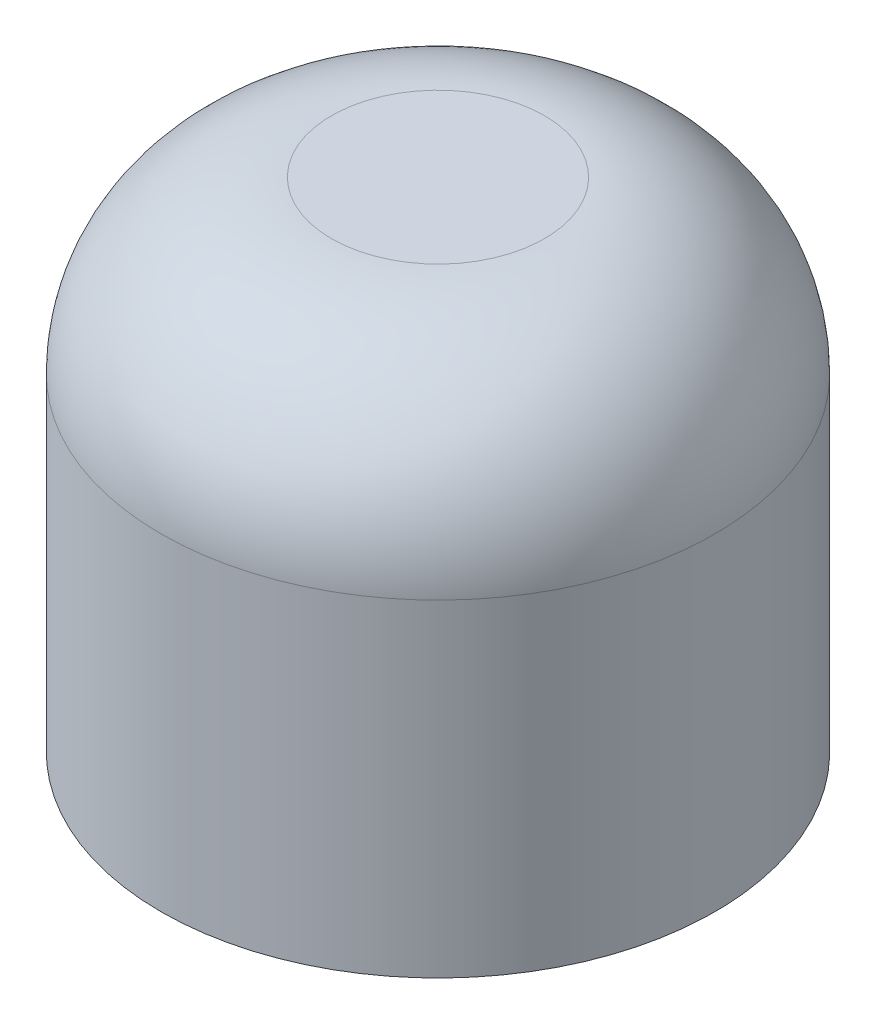
SolidWorks part; units mm, degrees
ref_plane "Front Plane" through (0, 0, 0) normal (0, 0, 1) x (1, 0, 0)
ref_plane "Top Plane" through (0, 0, 0) normal (0, 1, 0) x (1, 0, 0)
ref_plane "Right Plane" through (0, 0, 0) normal (1, 0, 0) x (0, 0, -1)
sketch "Sketch1" plane through (0, 0, 0) normal (0, 1, 0) x (1, 0, 0)
  circle A0 centre (0, 0) radius 13.65
  circle A1 centre (0, 0) radius 16.25
  dimension "D1" = 27.3
  dimension "D2" = 32.5
extrude "Boss-Extrude1" add sketch "Sketch1" along normal blind 24
sketch "Sketch2" plane through (0, 24, 0) normal (0, 1, 0) x (1, 0, 0)
  circle A0 centre (0, 0) radius 14.95
  dimension "D1" = 29.9
chamfer "Chamfer1" distance 1 angle 45 1 edges at (0, 0, 13.65)
sketch "Sketch3" plane through (0, 24, 0) normal (0, 1, 0) x (1, 0, 0)
  circle A0 centre (0, 0) radius 16.25
extrude "Boss-Extrude3" add sketch "Sketch3" along normal blind 5.2
fillet "Fillet3" radius 10 1 edges at (0, 29.2, 16.25)
equation "\"D2@Sketch1\"=\"D1@Sketch1\"+ 5.2"
